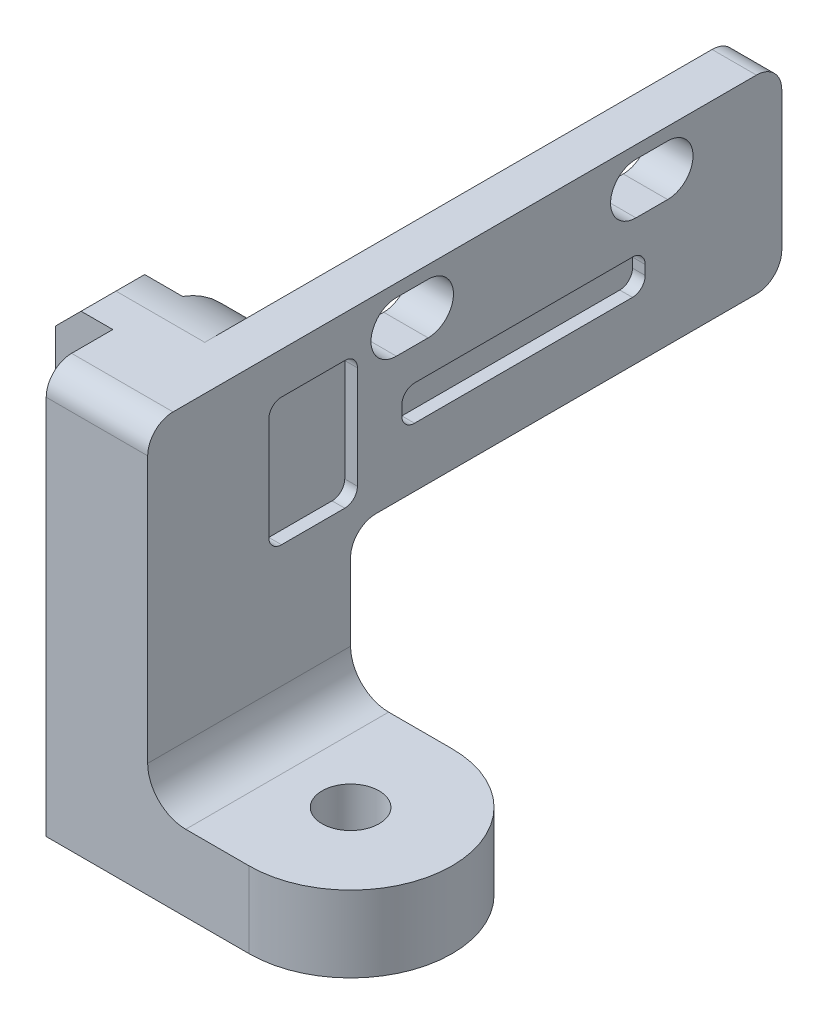
SolidWorks part; units mm, degrees
ref_plane "Front Plane" through (0, 0, 0) normal (0, 0, 1) x (1, 0, 0)
ref_plane "Top Plane" through (0, 0, 0) normal (0, 1, 0) x (1, 0, 0)
ref_plane "Right Plane" through (0, 0, 0) normal (1, 0, 0) x (0, 0, -1)
sketch "Sketch1" plane through (0, 0, 0) normal (1, 0, 0) x (0, 0, -1)
  line L0 (-32.8466, 14.9598) -> (-32.8466, -2.0885)
  line L1 (-29.2361, 26.9115) -> (-26.7361, 26.9115) construction
  line L2 (-29.2361, 28.9115) -> (-26.7361, 28.9115)
  line L4 (-29.2361, 24.9115) -> (-26.7361, 24.9115)
  line L5 (-32.8466, -2.0885) -> (-48.8466, -2.0885)
  line L6 (-48.8466, -2.0885) -> (-48.8466, 29.9115)
  line L8 (-48.8466, 29.9115) -> (1.1534, 29.9115)
  line L9 (-10.3466, 26.9115) -> (-7.8466, 26.9115) construction
  line L10 (-32.8466, 14.9598) -> (1.1534, 14.9598)
  line L11 (1.1534, 29.9115) -> (1.1534, 14.9598)
  line L12 (-10.3466, 28.9115) -> (-7.8466, 28.9115)
  line L16 (-10.3466, 24.9115) -> (-7.8466, 24.9115)
  arc A1 (-29.2361, 28.9115) -> (-29.2361, 24.9115) centre (-29.2361, 26.9115) ccw
  arc A2 (-10.3466, 28.9115) -> (-10.3466, 24.9115) centre (-10.3466, 26.9115) ccw
  arc A4 (-26.7361, 24.9115) -> (-26.7361, 28.9115) centre (-26.7361, 26.9115) ccw
  arc A5 (-7.8466, 24.9115) -> (-7.8466, 28.9115) centre (-7.8466, 26.9115) ccw
  point P0 (-27.9861, 26.9115)
  point P15 (-9.0966, 26.9115)
  dimension "D5" = 2
  dimension "D2" = 3
  dimension "D6" = 18.8895
  dimension "D7" = 9
  dimension "D8" = 2.5
  dimension "D9" = 16
  dimension "D10" = 32
  dimension "D11" = 50
extrude "Boss-Extrude1" add sketch "Sketch1" along normal blind 8
sketch "Sketch2" plane through (0, 0, 0) normal (-1, 0, 0) x (0, 0, 1)
  line L0 (40.8466, 5.9115) -> (40.8466, 13.9115) construction
  line L1 (48.8466, 29.9115) -> (48.8466, -2.0885) construction
  line L3 (38.0966, 29.9115) -> (43.5966, 29.9115)
  line L4 (38.0966, 29.9115) -> (38.0966, -2.0885)
  line L5 (38.0966, -2.0885) -> (43.5966, -2.0885)
  line L6 (43.5966, 29.9115) -> (43.5966, -2.0885)
  line L7 (38.0966, 29.9115) -> (43.5966, -2.0885) construction
  line L8 (38.0966, -2.0885) -> (43.5966, 29.9115) construction
  line L9 (48.8466, -2.0885) -> (32.8466, -2.0885) construction
  line L10 (-1.1534, 29.9115) -> (48.8466, 29.9115) construction
  point P5 (40.8466, 13.9115)
  dimension "D1" = 5.5
  dimension "D3" = 8
extrude "Boss-Extrude2" add sketch "Sketch2" along normal blind 4.5
sketch "Sketch4" plane through (8, 0, 0) normal (1, 0, 0) x (0, 0, -1)
  line L1 (-33.3061, 26.6479) -> (-38.2954, 26.6479)
  line L2 (-32.3061, 25.6479) -> (-32.3061, 17.5656)
  line L3 (-33.3061, 16.5656) -> (-38.2954, 16.5656)
  line L4 (-39.2954, 25.6479) -> (-39.2954, 17.5656)
  line L5 (-27.8064, 22.3683) -> (-10.6203, 22.3683)
  line L6 (-28.8064, 21.3683) -> (-28.8064, 20.6179)
  line L8 (-9.6203, 21.3683) -> (-9.6203, 20.6179)
  line L9 (-29.2361, 24.9115) -> (-26.7361, 24.9115) construction
  line L10 (-27.8064, 19.6179) -> (-10.6203, 19.6179)
  arc A0 (-32.3061, 17.5656) -> (-33.3061, 16.5656) centre (-33.3061, 17.5656) cw
  arc A1 (-38.2954, 16.5656) -> (-39.2954, 17.5656) centre (-38.2954, 17.5656) cw
  arc A2 (-38.2954, 26.6479) -> (-39.2954, 25.6479) centre (-38.2954, 25.6479) ccw
  arc A3 (-33.3061, 26.6479) -> (-32.3061, 25.6479) centre (-33.3061, 25.6479) cw
  arc A4 (-10.6203, 22.3683) -> (-9.6203, 21.3683) centre (-10.6203, 21.3683) cw
  arc A5 (-27.8064, 22.3683) -> (-28.8064, 21.3683) centre (-27.8064, 21.3683) ccw
  arc A6 (-10.6203, 19.6179) -> (-9.6203, 20.6179) centre (-10.6203, 20.6179) ccw
  arc A7 (-27.8064, 19.6179) -> (-28.8064, 20.6179) centre (-27.8064, 20.6179) cw
  dimension "D1" = 1
  dimension "D5" = 1
  dimension "D2" = 3.5431
  dimension "D3" = 4.2795
  dimension "D4" = 3.8028
extrude "Cut-Extrude2" cut sketch "Sketch4" against normal blind 1
sketch "Sketch5" plane through (0, 14.9598, 0) normal (0, -1, 0) x (1, 0, 0)
  line L0 (8, -1.1534) -> (0, -1.1534) construction
  line L1 (0, 32.8466) -> (4.5, 32.8466)
  line L2 (0, 32.8466) -> (0, -1.1534)
  line L3 (0, -1.1534) -> (4.5, -1.1534)
  line L4 (4.5, 32.8466) -> (4.5, -1.1534)
  dimension "D1" = 4.5
extrude "Cut-Extrude3" cut sketch "Sketch5" against normal through all
fillet "Fillet4" radius 2 4 edges at (6.25, 14.9598, 32.8466) (6.25, 14.9598, -1.1534) (6.25, 29.9115, -1.1534) (4, 29.9115, 48.8466)
chamfer "Chamfer1" distance 2 angle 45 2 edges at (-4.5, -2.0885, 40.8466) (-4.5, 29.9115, 40.8466)
sketch "Sketch6" plane through (0, -2.0885, 0) normal (0, -1, 0) x (1, 0, 0)
  line L0 (8, 48.8466) -> (16, 48.8466)
  line L2 (16, 32.8466) -> (8, 32.8466)
  line L3 (8, 32.8466) -> (8, 48.8466)
  arc A0 (16, 32.8466) -> (16, 48.8466) centre (16, 40.8466) ccw
  circle A1 centre (16, 40.8466) radius 2.25
  dimension "D2" = 4.5
  dimension "D1" = 8
extrude "Boss-Extrude3" add sketch "Sketch6" against normal blind 6 contours A0 L0 L3 L2
fillet "Fillet5" radius 8 1 edges at (2.25, 29.9115, 32.8466)
fillet "Fillet6" radius 3 1 edges at (8, 3.9115, 40.8466)
